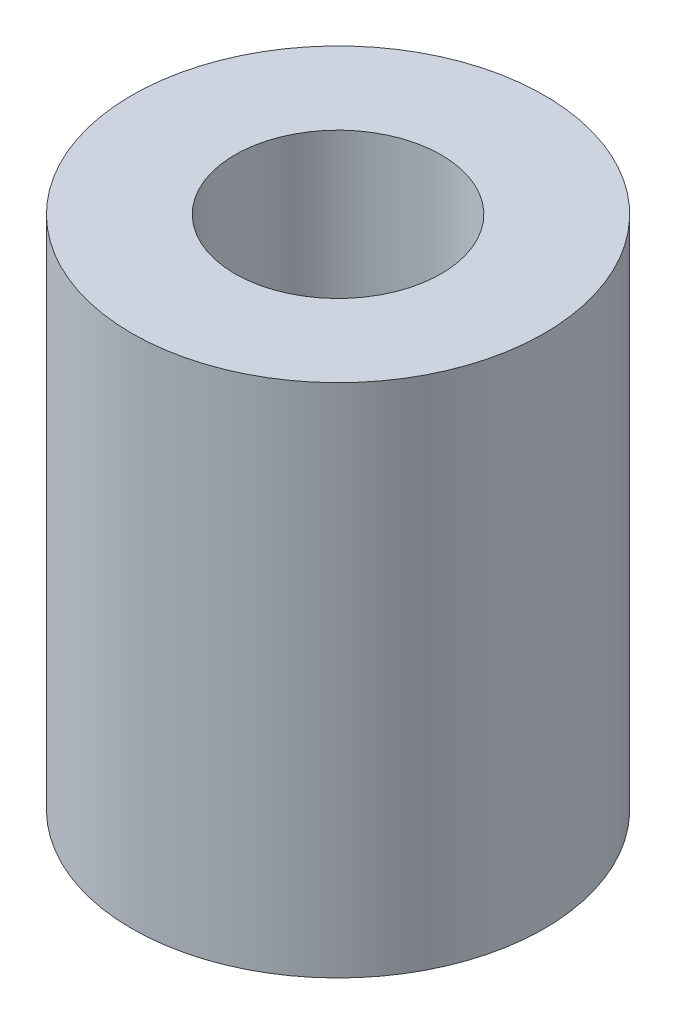
SolidWorks part; units mm, degrees
ref_plane "Front Plane" through (0, 0, 0) normal (0, 0, 1) x (1, 0, 0)
ref_plane "Top Plane" through (0, 0, 0) normal (0, 1, 0) x (1, 0, 0)
ref_plane "Right Plane" through (0, 0, 0) normal (1, 0, 0) x (0, 0, -1)
sketch "Sketch1" plane through (0, 0, 0) normal (0, 1, 0) x (1, 0, 0)
  circle A0 centre (0, 0) radius 6.35
  dimension "D1" = 12.7
extrude "Boss-Extrude1" add sketch "Sketch1" along normal blind 15.875
sketch "Sketch2" plane through (0, 15.875, 0) normal (0, 1, 0) x (1, 0, 0)
  circle A0 centre (0, 0) radius 3.175
  dimension "D1" = 6.35
extrude "Cut-Extrude1" cut sketch "Sketch2" against normal through all contours A0
